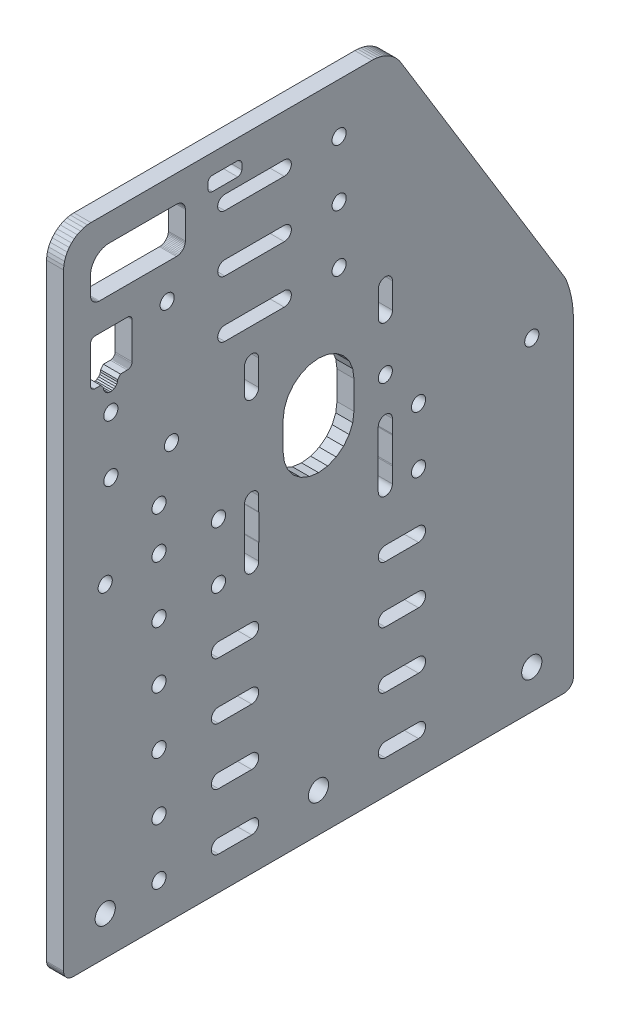
SolidWorks part; units mm, degrees
ref_plane "Front Plane" through (0, 0, 0) normal (0, 0, 1) x (1, 0, 0)
ref_plane "Top Plane" through (0, 0, 0) normal (0, 1, 0) x (1, 0, 0)
ref_plane "Right Plane" through (0, 0, 0) normal (1, 0, 0) x (0, 0, -1)
ref_plane "Plane1" through (0, 0, 0) normal (-1, 0, 0) x (0, -1, 0)
sketch "Sketch1" plane through (0, 0, 0) normal (-1, 0, 0) x (0, -1, 0)
  line L0 (-590.2121, -1614.2437) -> (-495.2304, -1672.3356)
  line L1 (-495.2304, -1672.3356) -> (-492.9855, -1673.1988)
  line L2 (-492.9855, -1673.1988) -> (-490.6881, -1673.9103)
  line L3 (-490.6881, -1673.9103) -> (-488.3483, -1674.4671)
  line L4 (-488.3483, -1674.4671) -> (-485.9766, -1674.8665)
  line L5 (-485.9766, -1674.8665) -> (-483.5835, -1675.1069)
  line L6 (-483.5835, -1675.1069) -> (-481.1798, -1675.1871)
  line L7 (-481.1798, -1675.1871) -> (-371.8266, -1675.1871)
  line L8 (-371.8266, -1675.1871) -> (-371.3877, -1675.1584)
  line L9 (-371.3877, -1675.1584) -> (-370.9562, -1675.0725)
  line L10 (-370.9562, -1675.0725) -> (-370.5397, -1674.9312)
  line L11 (-370.5397, -1674.9312) -> (-370.1452, -1674.7366)
  line L12 (-370.1452, -1674.7366) -> (-369.7795, -1674.4922)
  line L13 (-369.7795, -1674.4922) -> (-369.4487, -1674.2022)
  line L14 (-369.4487, -1674.2022) -> (-369.1587, -1673.8715)
  line L15 (-369.1587, -1673.8715) -> (-368.9143, -1673.5057)
  line L16 (-368.9143, -1673.5057) -> (-368.7198, -1673.1112)
  line L17 (-368.7198, -1673.1112) -> (-368.5784, -1672.6947)
  line L18 (-368.5784, -1672.6947) -> (-368.4926, -1672.2633)
  line L19 (-368.4926, -1672.2633) -> (-368.4638, -1671.8243)
  line L20 (-368.4638, -1671.8243) -> (-368.4638, -1498.5099)
  line L21 (-368.4638, -1498.5099) -> (-368.4926, -1498.071)
  line L22 (-368.4926, -1498.071) -> (-368.5784, -1497.6396)
  line L23 (-368.5784, -1497.6396) -> (-368.7198, -1497.223)
  line L24 (-368.7198, -1497.223) -> (-368.9143, -1496.8285)
  line L25 (-368.9143, -1496.8285) -> (-369.1587, -1496.4628)
  line L26 (-369.1587, -1496.4628) -> (-369.4487, -1496.1321)
  line L27 (-369.4487, -1496.1321) -> (-369.7795, -1495.842)
  line L28 (-369.7795, -1495.842) -> (-370.1452, -1495.5977)
  line L29 (-370.1452, -1495.5977) -> (-370.5397, -1495.4031)
  line L30 (-370.5397, -1495.4031) -> (-370.9562, -1495.2617)
  line L31 (-370.9562, -1495.2617) -> (-371.3877, -1495.1759)
  line L32 (-371.3877, -1495.1759) -> (-371.8266, -1495.1471)
  line L33 (-371.8266, -1495.1471) -> (-586.2881, -1495.1456)
  line L34 (-586.2881, -1495.1456) -> (-587.5497, -1495.2283)
  line L35 (-587.5497, -1495.2283) -> (-588.7897, -1495.475)
  line L36 (-588.7897, -1495.475) -> (-589.987, -1495.8813)
  line L37 (-589.987, -1495.8813) -> (-591.1209, -1496.4405)
  line L38 (-591.1209, -1496.4405) -> (-592.1721, -1497.1429)
  line L39 (-592.1721, -1497.1429) -> (-593.1227, -1497.9766)
  line L40 (-593.1227, -1497.9766) -> (-593.9563, -1498.9271)
  line L41 (-593.9563, -1498.9271) -> (-594.6588, -1499.9784)
  line L42 (-594.6588, -1499.9784) -> (-595.218, -1501.1123)
  line L43 (-595.218, -1501.1123) -> (-595.6244, -1502.3095)
  line L44 (-595.6244, -1502.3095) -> (-595.871, -1503.5495)
  line L45 (-595.871, -1503.5495) -> (-595.9537, -1504.8111)
  line L46 (-595.9537, -1504.8111) -> (-595.9537, -1603.9943)
  line L47 (-595.9537, -1603.9943) -> (-595.9102, -1605.016)
  line L48 (-595.9102, -1605.016) -> (-595.78, -1606.0302)
  line L49 (-595.78, -1606.0302) -> (-595.5641, -1607.0297)
  line L50 (-595.5641, -1607.0297) -> (-595.264, -1608.0073)
  line L51 (-595.264, -1608.0073) -> (-594.8819, -1608.9558)
  line L52 (-594.8819, -1608.9558) -> (-594.4205, -1609.8683)
  line L53 (-594.4205, -1609.8683) -> (-593.8833, -1610.7384)
  line L54 (-593.8833, -1610.7384) -> (-593.274, -1611.5596)
  line L55 (-593.274, -1611.5596) -> (-592.5971, -1612.3261)
  line L56 (-592.5971, -1612.3261) -> (-591.8575, -1613.0323)
  line L57 (-591.8575, -1613.0323) -> (-591.0606, -1613.673)
  line L58 (-591.0606, -1613.673) -> (-590.2121, -1614.2437)
  line L59 (-575.9778, -1552.0841) -> (-575.9778, -1573.0568)
  line L60 (-580.9777, -1573.098) -> (-580.9777, -1552.0841)
  line L61 (-535.9778, -1552.0854) -> (-535.9778, -1573.0582)
  line L62 (-540.9777, -1573.0993) -> (-540.9777, -1552.0854)
  line L63 (-555.9777, -1552.0992) -> (-555.9777, -1573.0855)
  line L64 (-560.9776, -1573.1131) -> (-560.9776, -1552.0992)
  line L65 (-524.9137, -1559.0552) -> (-515.9137, -1559.0552)
  line L66 (-515.9137, -1564.0552) -> (-524.9137, -1564.0552)
  line L67 (-524.9137, -1606.2991) -> (-515.9137, -1606.2991)
  line L68 (-515.9137, -1611.2991) -> (-524.9137, -1611.2991)
  line L69 (-477.6698, -1606.2991) -> (-468.6699, -1606.2991)
  line L70 (-468.6699, -1611.2991) -> (-477.6698, -1611.2991)
  line L71 (-477.6698, -1559.0528) -> (-468.6699, -1559.0552)
  line L72 (-468.6712, -1564.0782) -> (-477.6698, -1564.0758)
  line L73 (-586.0336, -1536.5791) -> (-586.215, -1536.2112)
  line L74 (-586.215, -1536.2112) -> (-586.3468, -1535.8228)
  line L75 (-586.3468, -1535.8228) -> (-586.4269, -1535.4204)
  line L76 (-586.4269, -1535.4204) -> (-586.4537, -1535.0111)
  line L77 (-586.4537, -1535.0111) -> (-586.4537, -1511.2962)
  line L78 (-586.4537, -1511.2962) -> (-586.3968, -1510.4284)
  line L79 (-586.3968, -1510.4284) -> (-586.2271, -1509.5753)
  line L80 (-586.2271, -1509.5753) -> (-585.9476, -1508.7517)
  line L81 (-585.9476, -1508.7517) -> (-585.5629, -1507.9717)
  line L82 (-585.5629, -1507.9717) -> (-585.0797, -1507.2485)
  line L83 (-585.0797, -1507.2485) -> (-584.5062, -1506.5946)
  line L84 (-584.5062, -1506.5946) -> (-583.8523, -1506.0211)
  line L85 (-583.8523, -1506.0211) -> (-583.1291, -1505.5379)
  line L86 (-583.1291, -1505.5379) -> (-582.3491, -1505.1533)
  line L87 (-582.3491, -1505.1533) -> (-581.5255, -1504.8737)
  line L88 (-581.5255, -1504.8737) -> (-580.6725, -1504.704)
  line L89 (-580.6725, -1504.704) -> (-579.8046, -1504.6471)
  line L90 (-579.8046, -1504.6471) -> (-573.6169, -1504.6471)
  line L91 (-573.6169, -1504.6471) -> (-573.2076, -1504.6739)
  line L92 (-573.2076, -1504.6739) -> (-572.8052, -1504.754)
  line L93 (-572.8052, -1504.754) -> (-572.4168, -1504.8858)
  line L94 (-572.4168, -1504.8858) -> (-572.0489, -1505.0673)
  line L95 (-572.0489, -1505.0673) -> (-571.7078, -1505.2952)
  line L96 (-571.7078, -1505.2952) -> (-571.3994, -1505.5656)
  line L97 (-571.3994, -1505.5656) -> (-571.1289, -1505.8741)
  line L98 (-571.1289, -1505.8741) -> (-570.901, -1506.2151)
  line L99 (-570.901, -1506.2151) -> (-570.7196, -1506.583)
  line L100 (-570.7196, -1506.583) -> (-570.5877, -1506.9715)
  line L101 (-570.5877, -1506.9715) -> (-570.5077, -1507.3738)
  line L102 (-570.5077, -1507.3738) -> (-570.4809, -1507.7831)
  line L103 (-570.4809, -1507.7831) -> (-570.4809, -1535.0111)
  line L104 (-570.4809, -1535.0111) -> (-570.5077, -1535.4204)
  line L105 (-570.5077, -1535.4204) -> (-570.5877, -1535.8228)
  line L106 (-570.5877, -1535.8228) -> (-570.7196, -1536.2112)
  line L107 (-570.7196, -1536.2112) -> (-570.901, -1536.5791)
  line L108 (-570.901, -1536.5791) -> (-571.1289, -1536.9202)
  line L109 (-571.1289, -1536.9202) -> (-571.3994, -1537.2286)
  line L110 (-571.3994, -1537.2286) -> (-571.7078, -1537.4991)
  line L111 (-571.7078, -1537.4991) -> (-572.0489, -1537.727)
  line L112 (-572.0489, -1537.727) -> (-572.4168, -1537.9084)
  line L113 (-572.4168, -1537.9084) -> (-572.8052, -1538.0403)
  line L114 (-572.8052, -1538.0403) -> (-573.2076, -1538.1203)
  line L115 (-573.2076, -1538.1203) -> (-573.6169, -1538.1471)
  line L116 (-573.6169, -1538.1471) -> (-583.3177, -1538.1471)
  line L117 (-583.3177, -1538.1471) -> (-583.727, -1538.1203)
  line L118 (-583.727, -1538.1203) -> (-584.1293, -1538.0403)
  line L119 (-584.1293, -1538.0403) -> (-584.5178, -1537.9084)
  line L120 (-584.5178, -1537.9084) -> (-584.8857, -1537.727)
  line L121 (-584.8857, -1537.727) -> (-585.2268, -1537.4991)
  line L122 (-585.2268, -1537.4991) -> (-585.5352, -1537.2286)
  line L123 (-585.5352, -1537.2286) -> (-585.8057, -1536.9202)
  line L124 (-585.8057, -1536.9202) -> (-586.0336, -1536.5791)
  line L125 (-560.5397, -1505.8783) -> (-560.4696, -1505.6715)
  line L126 (-560.4696, -1505.6715) -> (-560.373, -1505.4757)
  line L127 (-560.373, -1505.4757) -> (-560.2517, -1505.2942)
  line L128 (-560.2517, -1505.2942) -> (-560.1078, -1505.1301)
  line L129 (-560.1078, -1505.1301) -> (-559.9436, -1504.9862)
  line L130 (-559.9436, -1504.9862) -> (-559.7621, -1504.8649)
  line L131 (-559.7621, -1504.8649) -> (-559.5663, -1504.7683)
  line L132 (-559.5663, -1504.7683) -> (-559.3596, -1504.6981)
  line L133 (-559.3596, -1504.6981) -> (-559.1312, -1504.6471)
  line L134 (-559.1312, -1504.6471) -> (-558.9276, -1504.6413)
  line L135 (-558.9276, -1504.6413) -> (-548.4809, -1504.6452)
  line L136 (-548.4809, -1504.6452) -> (-545.8818, -1504.6452)
  line L137 (-545.8818, -1504.6452) -> (-545.6677, -1504.6877)
  line L138 (-545.6677, -1504.6877) -> (-545.461, -1504.7579)
  line L139 (-545.461, -1504.7579) -> (-545.2652, -1504.8545)
  line L140 (-545.2652, -1504.8545) -> (-545.0837, -1504.9758)
  line L141 (-545.0837, -1504.9758) -> (-544.9196, -1505.1197)
  line L142 (-544.9196, -1505.1197) -> (-544.7756, -1505.2838)
  line L143 (-544.7756, -1505.2838) -> (-544.6543, -1505.4654)
  line L144 (-544.6543, -1505.4654) -> (-544.5578, -1505.6612)
  line L145 (-544.5578, -1505.6612) -> (-544.4876, -1505.8679)
  line L146 (-544.4876, -1505.8679) -> (-544.445, -1506.082)
  line L147 (-544.445, -1506.082) -> (-544.4414, -1508.2677)
  line L148 (-544.4414, -1508.2677) -> (-543.221, -1509.2377)
  line L149 (-543.221, -1509.2377) -> (-542.574, -1509.3226)
  line L150 (-542.574, -1509.3226) -> (-541.9709, -1509.5721)
  line L151 (-541.9709, -1509.5721) -> (-541.453, -1509.9692)
  line L152 (-541.453, -1509.9692) -> (-541.0555, -1510.4868)
  line L153 (-541.0555, -1510.4868) -> (-540.8055, -1511.0897)
  line L154 (-540.8055, -1511.0897) -> (-540.72, -1511.7367)
  line L155 (-540.72, -1511.7367) -> (-540.805, -1512.3838)
  line L156 (-540.805, -1512.3838) -> (-541.0545, -1512.9868)
  line L157 (-541.0545, -1512.9868) -> (-541.4516, -1513.5047)
  line L158 (-541.4516, -1513.5047) -> (-541.9692, -1513.9022)
  line L159 (-541.9692, -1513.9022) -> (-542.572, -1514.1522)
  line L160 (-542.572, -1514.1522) -> (-543.219, -1514.2377)
  line L161 (-543.219, -1514.2377) -> (-544.4323, -1515.2077)
  line L162 (-544.4323, -1515.2077) -> (-544.4307, -1517.6776)
  line L163 (-544.4307, -1517.6776) -> (-544.4876, -1518.1096)
  line L164 (-544.4876, -1518.1096) -> (-544.5578, -1518.3163)
  line L165 (-544.5578, -1518.3163) -> (-544.6543, -1518.5121)
  line L166 (-544.6543, -1518.5121) -> (-544.7756, -1518.6936)
  line L167 (-544.7756, -1518.6936) -> (-544.9196, -1518.8578)
  line L168 (-544.9196, -1518.8578) -> (-545.0837, -1519.0017)
  line L169 (-545.0837, -1519.0017) -> (-545.2652, -1519.123)
  line L170 (-545.2652, -1519.123) -> (-545.461, -1519.2196)
  line L171 (-545.461, -1519.2196) -> (-545.6677, -1519.2897)
  line L172 (-545.6677, -1519.2897) -> (-546.0997, -1519.3486)
  line L173 (-546.0997, -1519.3486) -> (-558.9578, -1519.3427)
  line L174 (-558.9578, -1519.3427) -> (-559.1455, -1519.3427)
  line L175 (-559.1455, -1519.3427) -> (-559.3596, -1519.3001)
  line L176 (-559.3596, -1519.3001) -> (-559.5663, -1519.23)
  line L177 (-559.5663, -1519.23) -> (-559.7621, -1519.1334)
  line L178 (-559.7621, -1519.1334) -> (-559.9436, -1519.0121)
  line L179 (-559.9436, -1519.0121) -> (-560.1078, -1518.8682)
  line L180 (-560.1078, -1518.8682) -> (-560.2517, -1518.704)
  line L181 (-560.2517, -1518.704) -> (-560.373, -1518.5225)
  line L182 (-560.373, -1518.5225) -> (-560.4696, -1518.3267)
  line L183 (-560.4696, -1518.3267) -> (-560.5397, -1518.12)
  line L184 (-560.5397, -1518.12) -> (-560.5823, -1517.9059)
  line L185 (-560.5823, -1517.9059) -> (-560.5823, -1517.6796)
  line L186 (-560.5823, -1517.6796) -> (-560.568, -1506.084)
  line L187 (-560.568, -1506.084) -> (-560.5397, -1505.8783)
  line L188 (-512.6093, -1578.9371) -> (-510.6228, -1576.3483)
  line L189 (-510.6228, -1576.3483) -> (-508.034, -1574.3618)
  line L190 (-508.034, -1574.3618) -> (-505.0192, -1573.1131)
  line L191 (-505.0192, -1573.1131) -> (-501.784, -1572.6871)
  line L192 (-501.784, -1572.6871) -> (-491.784, -1572.6871)
  line L193 (-491.784, -1572.6871) -> (-488.5487, -1573.1131)
  line L194 (-488.5487, -1573.1131) -> (-485.534, -1574.3618)
  line L195 (-485.534, -1574.3618) -> (-482.9451, -1576.3483)
  line L196 (-482.9451, -1576.3483) -> (-480.9587, -1578.9371)
  line L197 (-480.9587, -1578.9371) -> (-479.7099, -1581.9519)
  line L198 (-479.7099, -1581.9519) -> (-479.284, -1585.1871)
  line L199 (-479.284, -1585.1871) -> (-479.7099, -1588.4224)
  line L200 (-479.7099, -1588.4224) -> (-480.9587, -1591.4371)
  line L201 (-480.9587, -1591.4371) -> (-482.9451, -1594.026)
  line L202 (-482.9451, -1594.026) -> (-485.534, -1596.0125)
  line L203 (-485.534, -1596.0125) -> (-488.5487, -1597.2612)
  line L204 (-488.5487, -1597.2612) -> (-491.784, -1597.6871)
  line L205 (-491.784, -1597.6871) -> (-501.784, -1597.6871)
  line L206 (-501.784, -1597.6871) -> (-505.0192, -1597.2612)
  line L207 (-505.0192, -1597.2612) -> (-508.034, -1596.0125)
  line L208 (-508.034, -1596.0125) -> (-510.6228, -1594.026)
  line L209 (-510.6228, -1594.026) -> (-512.6093, -1591.4371)
  line L210 (-512.6093, -1591.4371) -> (-513.858, -1588.4224)
  line L211 (-513.858, -1588.4224) -> (-514.284, -1585.1871)
  line L212 (-514.284, -1585.1871) -> (-513.858, -1581.9519)
  line L213 (-513.858, -1581.9519) -> (-512.6093, -1578.9371)
  line L214 (-588.9809, -1556.6482) -> (-588.9809, -1547.5504)
  line L215 (-587.544, -1546.1136) -> (-585.6436, -1546.0993)
  line L216 (-583.9746, -1547.7683) -> (-583.9889, -1556.6482)
  line L217 (-585.4257, -1558.085) -> (-587.544, -1558.085)
  arc A0 (-580.9777, -1552.0841) -> (-575.9778, -1552.0841) centre (-578.4777, -1552.0704) cw
  arc A1 (-575.9778, -1573.0568) -> (-580.9777, -1573.098) centre (-578.4777, -1573.0774) cw
  arc A2 (-540.9777, -1552.0854) -> (-535.9778, -1552.0854) centre (-538.4778, -1552.0718) cw
  arc A3 (-535.9778, -1573.0582) -> (-540.9777, -1573.0993) centre (-538.4778, -1573.0787) cw
  arc A4 (-560.9776, -1552.0992) -> (-555.9777, -1552.0992) centre (-558.4777, -1552.0856) cw
  arc A5 (-555.9777, -1573.0855) -> (-560.9776, -1573.1131) centre (-558.4777, -1573.0993) cw
  arc A6 (-515.9137, -1559.0552) -> (-515.9137, -1564.0552) centre (-515.9137, -1561.5552) cw
  arc A7 (-524.9137, -1564.0552) -> (-524.9137, -1559.0552) centre (-524.9137, -1561.5552) cw
  arc A8 (-515.9137, -1606.2991) -> (-515.9137, -1611.2991) centre (-515.9137, -1608.7991) cw
  arc A9 (-524.9137, -1611.2991) -> (-524.9137, -1606.2991) centre (-524.9137, -1608.7991) cw
  arc A10 (-468.6699, -1606.2991) -> (-468.6699, -1611.2991) centre (-468.6699, -1608.7991) cw
  arc A11 (-477.6698, -1611.2991) -> (-477.6698, -1606.2991) centre (-477.6698, -1608.7991) cw
  arc A12 (-468.6699, -1559.0552) -> (-468.6712, -1564.0782) centre (-468.6705, -1561.5667) cw
  arc A13 (-477.6698, -1564.0758) -> (-477.6698, -1559.0528) centre (-477.6692, -1561.5643) cw
  circle A14 centre (-382.1591, -1509.8471) radius 3.5685
  circle A15 centre (-382.1591, -1585.1671) radius 3.5685
  circle A16 centre (-382.1591, -1660.4871) radius 3.5685
  circle A17 centre (-538.3993, -1592.4578) radius 2.5
  circle A18 centre (-558.4485, -1592.4578) radius 2.5
  circle A19 centre (-578.4485, -1592.4578) radius 2.5
  circle A20 centre (-534.4436, -1511.8471) radius 2.5
  circle A21 centre (-558.4024, -1531.723) radius 2.5
  circle A22 centre (-514.4436, -1511.8471) radius 2.5
  circle A23 centre (-514.4436, -1533.239) radius 2.5
  circle A24 centre (-497.4962, -1528.8471) radius 2.5
  circle A25 centre (-482.7991, -1549.8471) radius 2.5
  circle A26 centre (-482.7991, -1509.8471) radius 2.5
  circle A27 centre (-482.7991, -1620.4871) radius 2.5
  circle A28 centre (-482.7991, -1660.4871) radius 2.5
  circle A29 centre (-402.4962, -1528.8471) radius 2.5
  arc A30 (-588.9809, -1547.5504) -> (-587.544, -1546.1136) centre (-587.3137, -1547.7807) cw
  arc A31 (-585.6436, -1546.0993) -> (-583.9746, -1547.7683) centre (-585.6436, -1547.7683) cw
  arc A32 (-583.9889, -1556.6482) -> (-585.4257, -1558.085) centre (-585.656, -1556.4179) cw
  arc A33 (-587.544, -1558.085) -> (-588.9809, -1556.6482) centre (-587.3262, -1556.4303) cw
extrude "Boss-Extrude1" add sketch "Sketch1" against normal blind 6
sketch "Sketch2" plane through (6, 0, 0) normal (1, 0, 0) x (0, 0, -1)
  line L0 (1561.5671, 482.7991) -> (1561.5671, 462.7991) construction
  line L1 (1564.0671, 482.7991) -> (1564.0671, 462.7991)
  line L2 (1559.0671, 482.7991) -> (1559.0671, 462.7991)
  line L3 (1608.7671, 482.7991) -> (1608.7671, 462.7991) construction
  line L4 (1611.2671, 482.7991) -> (1611.2671, 462.7991)
  line L5 (1606.2671, 482.7991) -> (1606.2671, 462.7991)
  line L6 (1620.4871, 442.7991) -> (1608.7671, 442.7991) construction
  line L7 (1620.4871, 440.2991) -> (1608.7671, 440.2991)
  line L8 (1620.4871, 445.2991) -> (1608.7671, 445.2991)
  line L9 (1620.4871, 422.7991) -> (1608.7671, 422.7991) construction
  line L10 (1620.4871, 420.2991) -> (1608.7671, 420.2991)
  line L11 (1620.4871, 425.2991) -> (1608.7671, 425.2991)
  line L12 (1620.4871, 402.7991) -> (1608.7671, 402.7991) construction
  line L13 (1620.4871, 400.2991) -> (1608.7671, 400.2991)
  line L14 (1620.4871, 405.2991) -> (1608.7671, 405.2991)
  line L15 (1620.4871, 382.7991) -> (1608.7671, 382.7991) construction
  line L16 (1620.4871, 380.2991) -> (1608.7671, 380.2991)
  line L17 (1620.4871, 385.2991) -> (1608.7671, 385.2991)
  line L18 (1561.5671, 442.7991) -> (1549.8471, 442.7991) construction
  line L19 (1561.5671, 440.2991) -> (1549.8471, 440.2991)
  line L20 (1561.5671, 445.2991) -> (1549.8471, 445.2991)
  line L21 (1561.5671, 422.7991) -> (1549.8471, 422.7991) construction
  line L22 (1561.5671, 420.2991) -> (1549.8471, 420.2991)
  line L23 (1561.5671, 425.2991) -> (1549.8471, 425.2991)
  line L24 (1561.5671, 402.7991) -> (1549.8471, 402.7991) construction
  line L25 (1561.5671, 400.2991) -> (1549.8471, 400.2991)
  line L26 (1561.5671, 405.2991) -> (1549.8471, 405.2991)
  line L27 (1561.5671, 382.7991) -> (1549.8471, 382.7991) construction
  line L28 (1561.5671, 380.2991) -> (1549.8471, 380.2991)
  line L29 (1561.5671, 385.2991) -> (1549.8471, 385.2991)
  circle A0 centre (1608.7671, 442.7991) radius 2.5 construction
  circle A26 centre (1620.4871, 402.7991) radius 2.5 construction
  circle A27 centre (1620.4871, 482.7991) radius 2.5 construction
  circle A28 centre (1549.8471, 482.7991) radius 2.5 construction
  circle A29 centre (1620.4871, 482.7991) radius 2.5
  circle A30 centre (1549.8471, 482.7991) radius 2.5
  arc A32 (1564.0671, 482.7991) -> (1559.0671, 482.7991) centre (1561.5671, 482.7991) ccw
  circle A35 centre (1549.8471, 462.7991) radius 2.5
  circle A36 centre (1620.4871, 462.7991) radius 2.5
  circle A39 centre (1549.8471, 442.7991) radius 2.5 construction
  circle A40 centre (1620.4871, 442.7991) radius 2.5 construction
  circle A43 centre (1549.8471, 422.7991) radius 2.5 construction
  circle A44 centre (1620.4871, 422.7991) radius 2.5 construction
  circle A47 centre (1549.8471, 402.7991) radius 2.5 construction
  circle A49 centre (1549.8471, 382.7991) radius 2.5 construction
  circle A51 centre (1620.4871, 382.7991) radius 2.5 construction
  circle A52 centre (1608.7671, 422.7991) radius 2.5 construction
  circle A53 centre (1608.7671, 382.7991) radius 2.5 construction
  arc A54 (1559.0671, 462.7991) -> (1564.0671, 462.7991) centre (1561.5671, 462.7991) ccw
  circle A55 centre (1561.5671, 442.7991) radius 2.5 construction
  circle A56 centre (1561.5671, 422.7991) radius 2.5 construction
  circle A57 centre (1561.5671, 402.7991) radius 2.5 construction
  circle A58 centre (1561.5671, 382.7991) radius 2.5 construction
  circle A61 centre (1608.7671, 402.7991) radius 2.5 construction
  arc A62 (1611.2671, 482.7991) -> (1606.2671, 482.7991) centre (1608.7671, 482.7991) ccw
  arc A63 (1606.2671, 462.7991) -> (1611.2671, 462.7991) centre (1608.7671, 462.7991) ccw
  arc A64 (1611.2671, 482.7991) -> (1606.2671, 482.7991) centre (1608.7671, 482.7991) ccw
  arc A65 (1606.2671, 462.7991) -> (1611.2671, 462.7991) centre (1608.7671, 462.7991) ccw
  circle A66 centre (1528.8471, 497.4962) radius 2.5 construction
  circle A67 centre (1528.8471, 497.4962) radius 2.5
  circle A68 centre (1608.7671, 497.4962) radius 2.5
  circle A69 centre (1528.8471, 482.7962) radius 2.5
  circle A70 centre (1528.8471, 462.7861) radius 2.5
  circle A71 centre (1528.8471, 442.7761) radius 2.5
  circle A72 centre (1528.8471, 422.766) radius 2.5
  circle A74 centre (1528.8471, 382.7459) radius 2.5
  circle A75 centre (1528.8471, 402.756) radius 2.5 [skipped]
  arc A76 (1620.4871, 440.2991) -> (1620.4871, 445.2991) centre (1620.4871, 442.7991) ccw
  arc A77 (1608.7671, 445.2991) -> (1608.7671, 440.2991) centre (1608.7671, 442.7991) ccw
  arc A78 (1620.4871, 420.2991) -> (1620.4871, 425.2991) centre (1620.4871, 422.7991) ccw
  arc A79 (1608.7671, 425.2991) -> (1608.7671, 420.2991) centre (1608.7671, 422.7991) ccw
  arc A80 (1620.4871, 400.2991) -> (1620.4871, 405.2991) centre (1620.4871, 402.7991) ccw
  arc A81 (1608.7671, 405.2991) -> (1608.7671, 400.2991) centre (1608.7671, 402.7991) ccw
  arc A82 (1620.4871, 380.2991) -> (1620.4871, 385.2991) centre (1620.4871, 382.7991) ccw
  arc A83 (1608.7671, 385.2991) -> (1608.7671, 380.2991) centre (1608.7671, 382.7991) ccw
  arc A84 (1561.5671, 440.2991) -> (1561.5671, 445.2991) centre (1561.5671, 442.7991) ccw
  arc A85 (1549.8471, 445.2991) -> (1549.8471, 440.2991) centre (1549.8471, 442.7991) ccw
  arc A86 (1561.5671, 420.2991) -> (1561.5671, 425.2991) centre (1561.5671, 422.7991) ccw
  arc A87 (1549.8471, 425.2991) -> (1549.8471, 420.2991) centre (1549.8471, 422.7991) ccw
  arc A88 (1561.5671, 400.2991) -> (1561.5671, 405.2991) centre (1561.5671, 402.7991) ccw
  arc A89 (1549.8471, 405.2991) -> (1549.8471, 400.2991) centre (1549.8471, 402.7991) ccw
  arc A90 (1561.5671, 380.2991) -> (1561.5671, 385.2991) centre (1561.5671, 382.7991) ccw
  arc A91 (1549.8471, 385.2991) -> (1549.8471, 380.2991) centre (1549.8471, 382.7991) ccw
  point P19 (1608.7671, 472.7991)
  point P48 (1614.6271, 442.7991)
  point P54 (1561.5671, 472.7991)
  point P80 (1614.6271, 422.7991)
  point P85 (1614.6271, 402.7991)
  point P92 (1614.6271, 382.7991)
  point P97 (1555.7071, 442.7991)
  point P102 (1555.7071, 422.7991)
  point P107 (1555.7071, 402.7991)
  point P112 (1555.7071, 382.7991)
  dimension "D2" = 6
  dimension "D4" = 79.92
  dimension "D6" = 3
  dimension "D7" = 2
  dimension "D9" = 2
  dimension "D10" = 14.7
  dimension "D11" = 6
  dimension "D12" = 2
  dimension "D13" = 5
  dimension "D14" = 11.72
  dimension "D15" = 2
  dimension "D3" = 2
  dimension "D16" = 5
  dimension "D17" = 11.72
  dimension "D18" = 5
  dimension "D19" = 11.72
  dimension "D20" = 5
  dimension "D21" = 11.72
  dimension "D22" = 5
  dimension "D23" = 11.72
  dimension "D24" = 5
  dimension "D25" = 11.72
  dimension "D26" = 5
  dimension "D27" = 11.72
  dimension "D28" = 5
  dimension "D29" = 11.72
  dimension "D5" = 4
  dimension "D8" = 2
extrude "Cut-Extrude3" cut sketch "Sketch2" against normal through all contours L5 A63 L4 A62 | A39 | A30 | A35 | A43 | A47 | A49 | A58 | A57 | A56 | A55 | L1 A54 L2 A32 | A36 | A61 | A53 | A51 | A26 | A44 | A52 | A0 | A40 | A29 | A68 | A74 | A70 | A71 | A69 | A72 | L8 A77 L7 A76 | L11 A79 L10 A78 | L14 A81 L13 A80 | L17 A82 L16 A83 | L29 A91 L28 A90 | L26 A89 L25 A88 | L23 A87 L22 A86 | L20 A85 L19 A84
